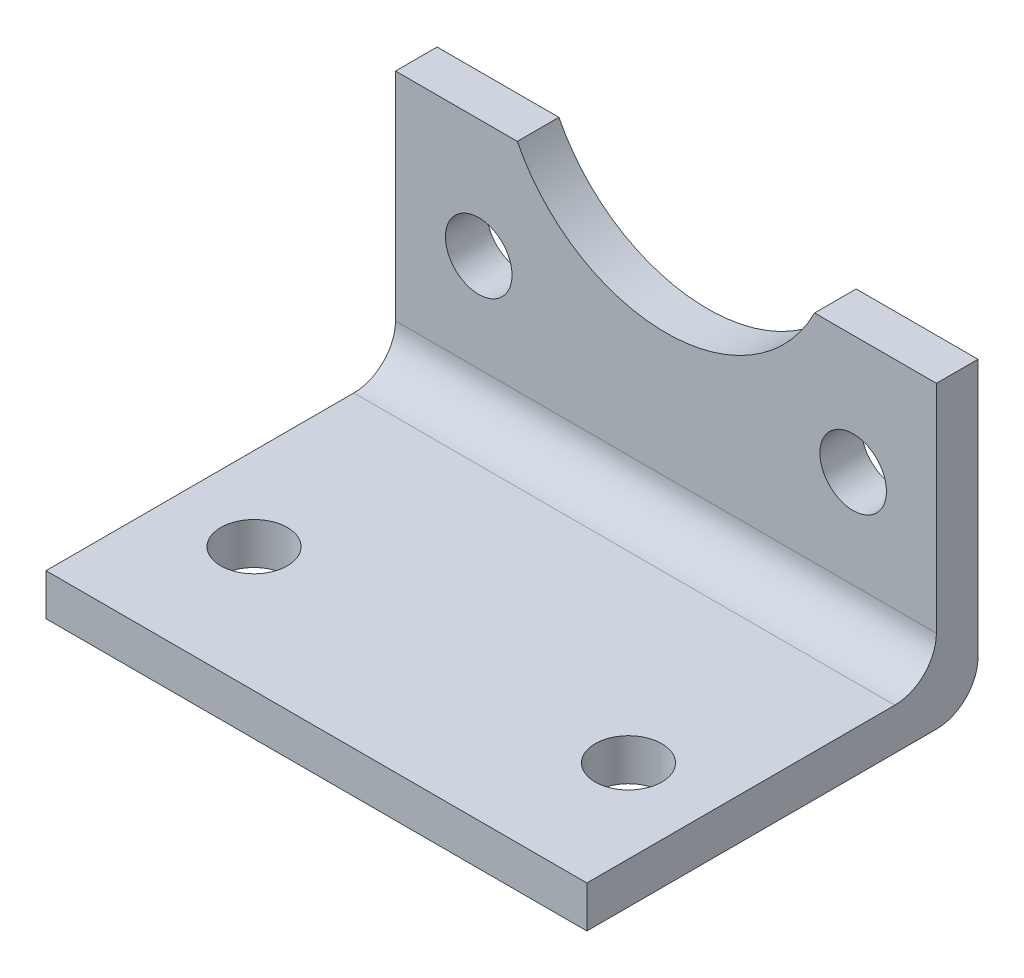
SolidWorks part; units mm, degrees
ref_plane "Płaszczyzna przednia" through (0, 0, 0) normal (0, 0, 1) x (1, 0, 0)
ref_plane "Płaszczyzna górna" through (0, 0, 0) normal (0, 1, 0) x (1, 0, 0)
ref_plane "Płaszczyzna prawa" through (0, 0, 0) normal (1, 0, 0) x (0, 0, -1)
sketch "Szkic1" plane through (0, 0, 0) normal (0, 0, 1) x (1, 0, 0)
  line L0 (17.8606, 18) -> (32.5, 18)
  line L1 (-32.5, 18) -> (-17.8606, 18)
  line L2 (-32.5, 18) -> (-32.5, -18)
  line L3 (-32.5, -18) -> (32.5, -18)
  line L4 (32.5, 18) -> (32.5, -18)
  line L5 (-32.5, 18) -> (32.5, -18) construction
  line L6 (-32.5, -18) -> (32.5, 18) construction
  line L7 (0, -55) -> (0, 55) construction
  circle A0 centre (-22.5, 3.75) radius 4
  arc A1 (-17.8606, 18) -> (17.8606, 18) centre (0, 27) ccw
  circle A2 centre (22.5, 3.75) radius 4
  point P0 (0, 0)
  point P8 (0, 27)
  dimension "D3" = 8
  dimension "D7" = 20
  dimension "D1" = 65
  dimension "D2" = 36
  dimension "D4" = 22.5
  dimension "D5" = 23.25
  dimension "D6" = 45
extrude "Dodanie-wyciągnięcie1" add sketch "Szkic1" against normal blind 5
sketch "Szkic2" plane through (0, -18, 0) normal (0, -1, 0) x (1, 0, 0)
  line L0 (-32.5, -5) -> (32.5, -5)
  line L5 (-32.5, -5) -> (-32.5, 42)
  line L6 (32.5, -5) -> (32.5, 42)
  line L7 (-32.5, 42) -> (32.5, 42)
  line L8 (0, -2.75) -> (0, 2.75) construction
  circle A0 centre (-22.5, 27) radius 4
  circle A1 centre (22.5, 27) radius 4
  dimension "D2" = 8
  dimension "D1" = 47
  dimension "D3" = 22.5
  dimension "D4" = 32
extrude "Dodanie-wyciągnięcie2" add sketch "Szkic2" against normal blind 5
fillet "Zaokrąglenie1" radius 5 1 edges at (0, -13, 0)
fillet "Zaokrąglenie2" radius 5 1 edges at (0, -18, -5)
